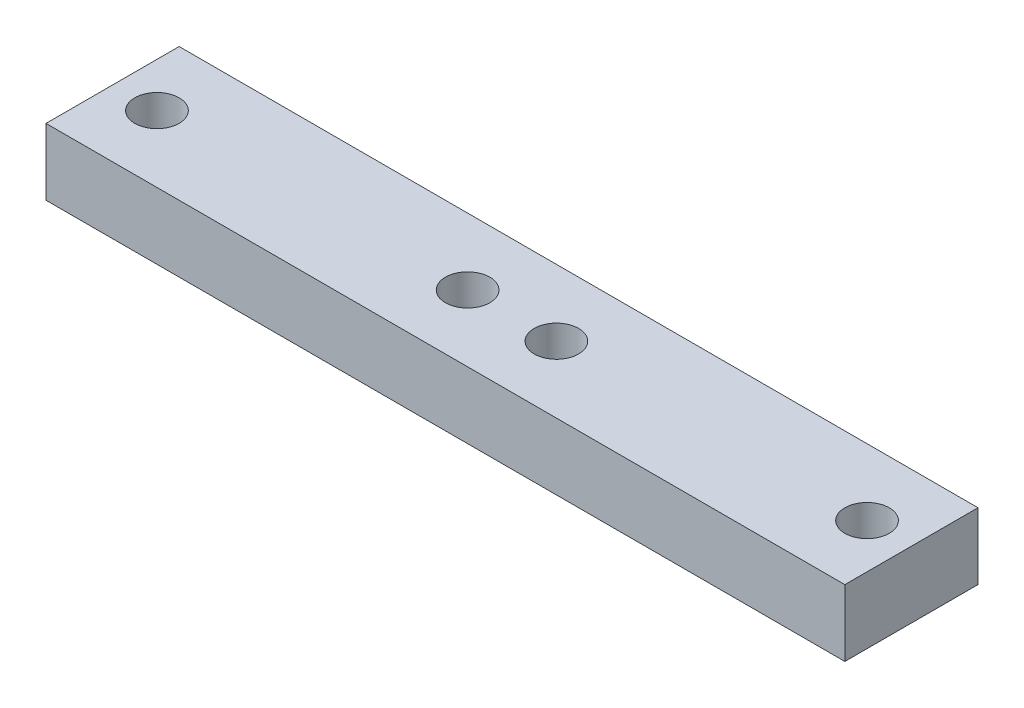
SolidWorks part; units mm, degrees
ref_plane "Front Plane" through (0, 0, 0) normal (0, 0, 1) x (1, 0, 0)
ref_plane "Top Plane" through (0, 0, 0) normal (0, 1, 0) x (1, 0, 0)
ref_plane "Right Plane" through (0, 0, 0) normal (1, 0, 0) x (0, 0, -1)
sketch "Sketch1" plane through (0, 0, 0) normal (0, 1, 0) x (1, 0, 0)
  line L0 (-36, 0) -> (36, 0) construction
  line L1 (36, -6) -> (-36, -6)
  line L2 (36, -6) -> (36, 6)
  line L3 (36, 6) -> (-36, 6)
  line L4 (-36, -6) -> (-36, 6)
  line L5 (36, -6) -> (-36, 6) construction
  line L6 (36, 6) -> (-36, -6) construction
  line L7 (0, 6) -> (0, -6) construction
  line L8 (4, 6) -> (4, -6) construction
  line L9 (32, 6) -> (32, -6) construction
  line L10 (0, 5.836) -> (4, 5.836) construction
  line L11 (32, 5.836) -> (36, 5.836) construction
  circle A0 centre (32, 0) radius 2
  circle A1 centre (4, 0) radius 2
  circle A2 centre (-4, 0) radius 2
  circle A3 centre (-32, 0) radius 2
  point P0 (0, 0)
  dimension "D1" = 4
  dimension "D2" = 28
  dimension "D3" = 36
  dimension "D4" = 6
extrude "Boss-Extrude1" add sketch "Sketch1" along normal blind 6
